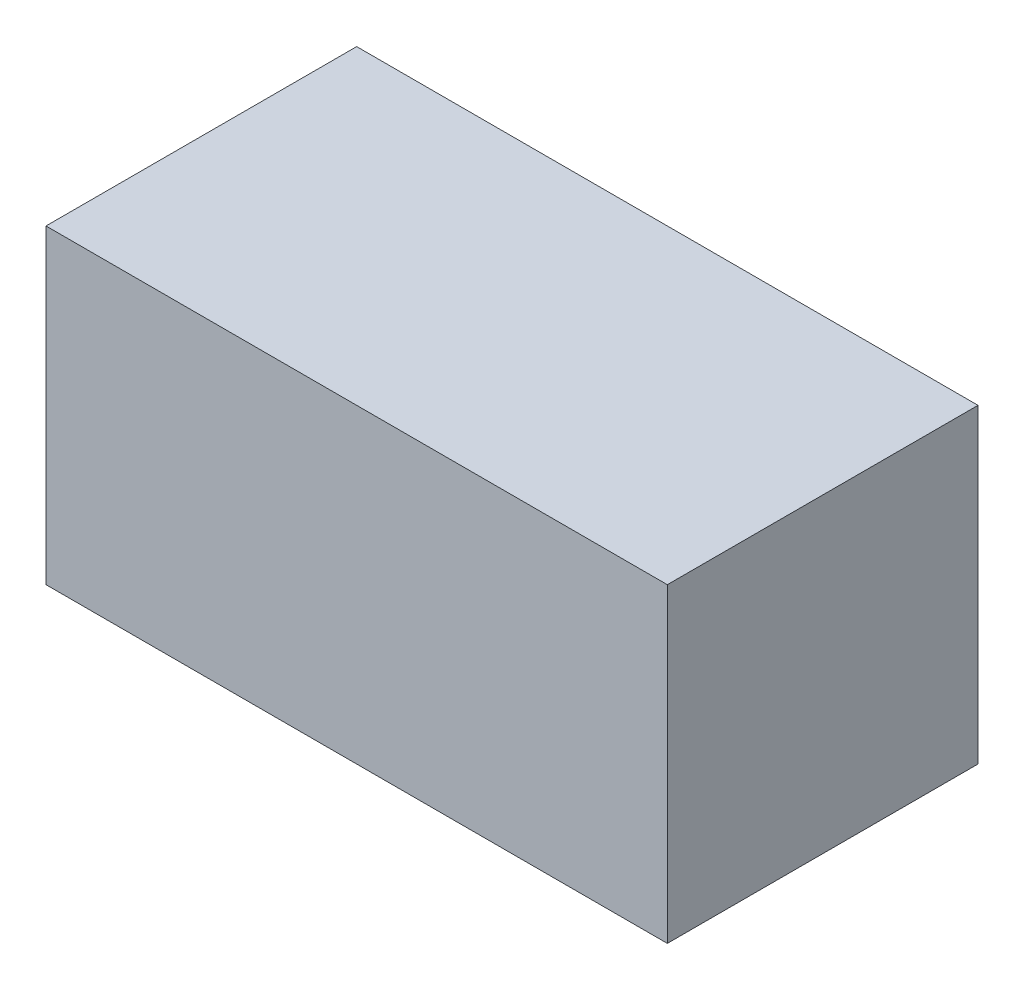
SolidWorks part; units mm, degrees
ref_plane "Front Plane" through (0, 0, 0) normal (0, 0, 1) x (1, 0, 0)
ref_plane "Top Plane" through (0, 0, 0) normal (0, 1, 0) x (1, 0, 0)
ref_plane "Right Plane" through (0, 0, 0) normal (1, 0, 0) x (0, 0, -1)
sketch "Sketch1" plane through (0, 0, 0) normal (0, 1, 0) x (1, 0, 0)
  line L1 (0, 0) -> (0.8, 0)
  line L2 (0, 0) -> (0, 0.4)
  line L3 (0, 0.4) -> (0.8, 0.4)
  line L4 (0.8, 0) -> (0.8, 0.4)
  dimension "D1" = 0.8
  dimension "D2" = 0.4
extrude "Boss-Extrude1" add sketch "Sketch1" along normal blind 0.4
